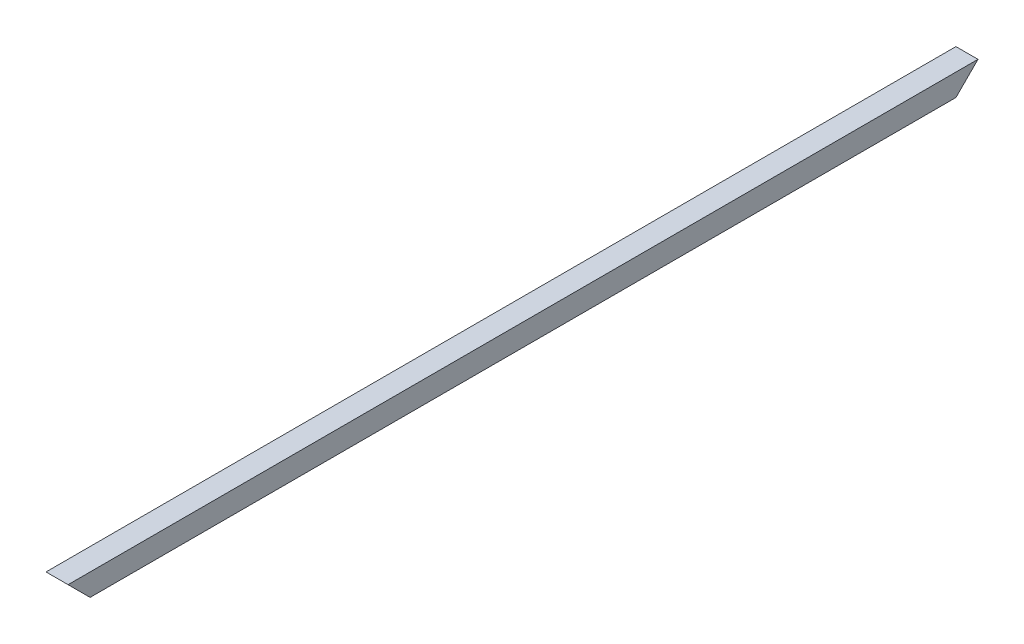
SolidWorks part; units mm, degrees
ref_plane "Front Plane" through (0, 0, 0) normal (0, 0, 1) x (1, 0, 0)
ref_plane "Top Plane" through (0, 0, 0) normal (0, 1, 0) x (1, 0, 0)
ref_plane "Right Plane" through (0, 0, 0) normal (1, 0, 0) x (0, 0, -1)
sketch "Sketch1" plane through (0, 0, 0) normal (0, 0, 1) x (1, 0, 0)
  line L0 (-38, 1629.5) -> (-2, 1629.5)
  line L1 (-40, 1631.5) -> (0, 1631.5)
  line L2 (-40, 1631.5) -> (-40, 1591.5)
  line L3 (-40, 1591.5) -> (0, 1591.5)
  line L4 (0, 1631.5) -> (0, 1591.5)
  line L5 (-2, 1629.5) -> (-2, 1593.5)
  line L6 (-38, 1593.5) -> (-2, 1593.5)
  line L7 (-38, 1629.5) -> (-38, 1593.5)
  dimension "D1" = 2
extrude "Boss-Extrude1" add sketch "Sketch1" against normal blind 1650
sketch "Sketch2" plane through (0, 0, 0) normal (1, 0, 0) x (0, 0, -1)
  line L0 (0, 1631.5) -> (0, 1591.5)
  line L1 (0, 1591.5) -> (40, 1591.5)
  line L2 (1650, 1591.5) -> (0, 1591.5) construction
  line L3 (40, 40) -> (40, 1591.5) construction
  line L4 (40, 1591.5) -> (0, 1631.5)
  line L5 (825, 1631.5) -> (825, 1591.5) construction
  line L6 (1650, 1631.5) -> (0, 1631.5) construction
  line L7 (1610, 1591.5) -> (1650, 1631.5)
  line L8 (1650, 1591.5) -> (1610, 1591.5)
  line L9 (1650, 1631.5) -> (1650, 1591.5)
extrude "Cut-Extrude1" cut sketch "Sketch2" against normal up to surface (40 mm away) up to face at (-40, 1611.5, -825)
